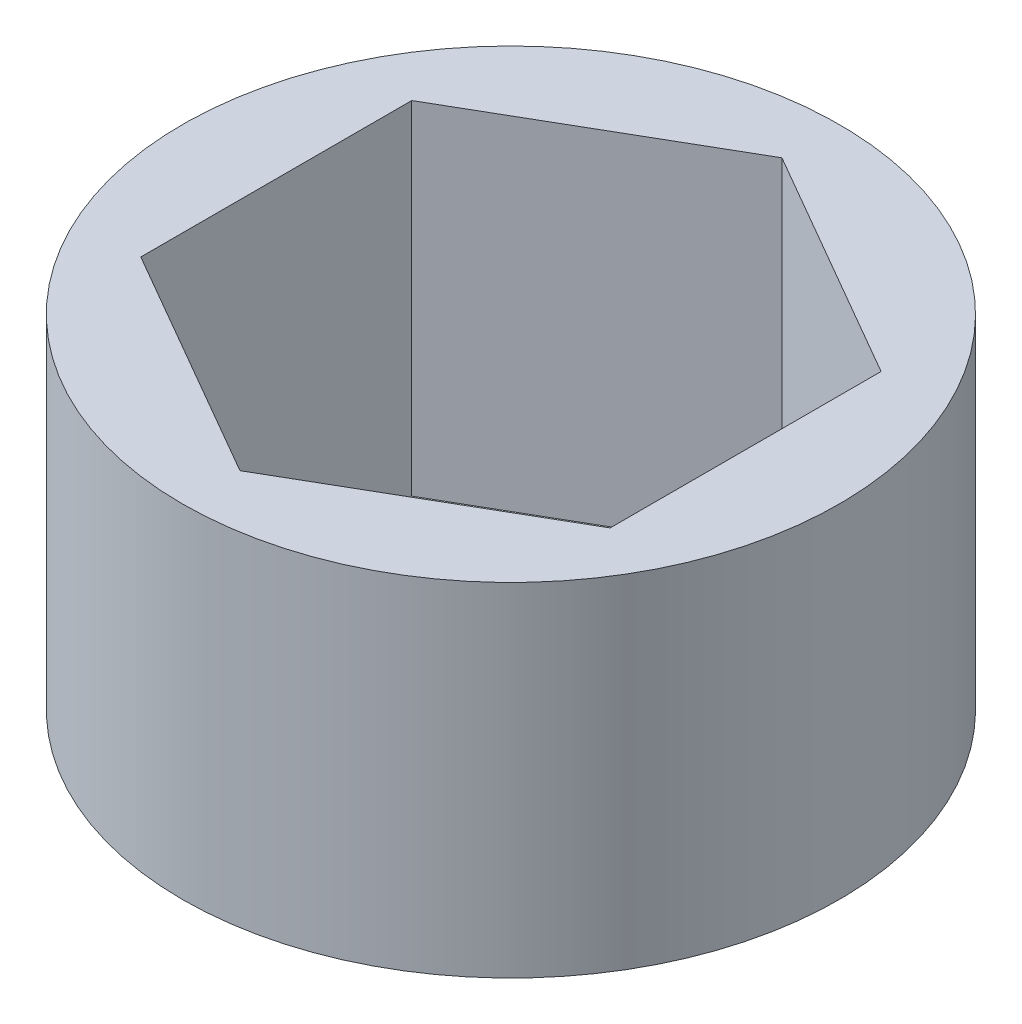
SolidWorks part; units mm, degrees
material "PET"
ref_plane "Front Plane" through (0, 0, 0) normal (0, 0, 1) x (1, 0, 0)
ref_plane "Top Plane" through (0, 0, 0) normal (0, 1, 0) x (1, 0, 0)
ref_plane "Right Plane" through (0, 0, 0) normal (1, 0, 0) x (0, 0, -1)
sketch "Sketch1" plane through (0, 0, 0) normal (0, 1, 0) x (1, 0, 0)
  line L1 (0, 7.3323) -> (-6.35, 3.6662)
  line L2 (-6.35, 3.6662) -> (-6.35, -3.6662)
  line L3 (-6.35, -3.6662) -> (0, -7.3323)
  line L4 (0, -7.3323) -> (6.35, -3.6662)
  line L5 (6.35, -3.6662) -> (6.35, 3.6662)
  line L6 (6.35, 3.6662) -> (0, 7.3323)
  circle A0 centre (0, 0) radius 8.89
  circle A2 centre (0, 0) radius 6.35 construction
  point P3 (0, 0)
  dimension "D1" = 12.7
  dimension "D2" = 17.78
extrude "Boss-Extrude1" add sketch "Sketch1" along normal mid plane 9.271
